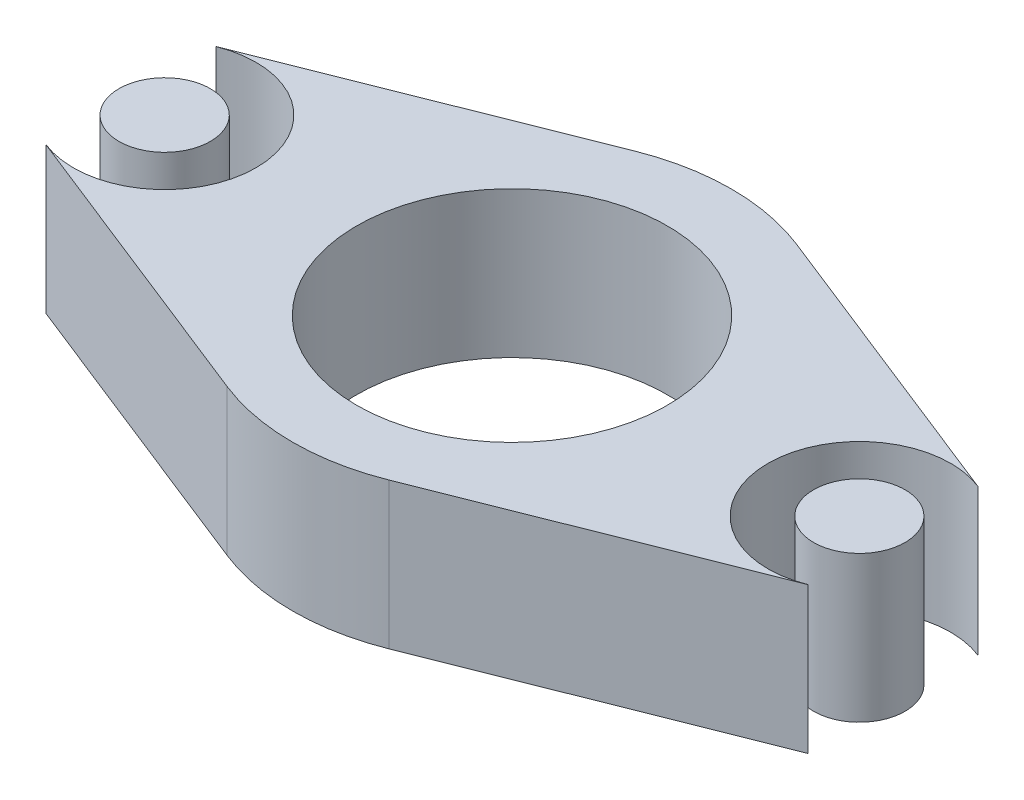
SolidWorks part; units mm, degrees
ref_plane "Front Plane" through (0, 0, 0) normal (0, 0, 1) x (1, 0, 0)
ref_plane "Top Plane" through (0, 0, 0) normal (0, 1, 0) x (1, 0, 0)
ref_plane "Right Plane" through (0, 0, 0) normal (1, 0, 0) x (0, 0, -1)
sketch "Sketch2" plane through (0, 0, 0) normal (0, 1, 0) x (1, 0, 0)
  line L0 (-22.1053, 55.7795) -> (-104.2105, 23.2415)
  line L1 (-22.1053, -55.7795) -> (-104.2105, -23.2415)
  line L2 (0, 0) -> (0, 60) construction
  line L3 (22.1053, -55.7795) -> (104.2105, -23.2415)
  line L4 (22.1053, 55.7795) -> (104.2105, 23.2415)
  circle A0 centre (0, 0) radius 42.5
  circle A1 centre (0, 0) radius 60
  circle A3 centre (-95, 0) radius 25
  circle A5 centre (-95, 0) radius 12.5
  circle A6 centre (95, 0) radius 12.5
  circle A7 centre (95, 0) radius 25
  dimension "D2" = 25
  dimension "D3" = 190
  dimension "D4" = 120
  dimension "D5" = 85
  dimension "D1" = 50
extrude "Boss-Extrude1" add sketch "Sketch2" along normal blind 40
